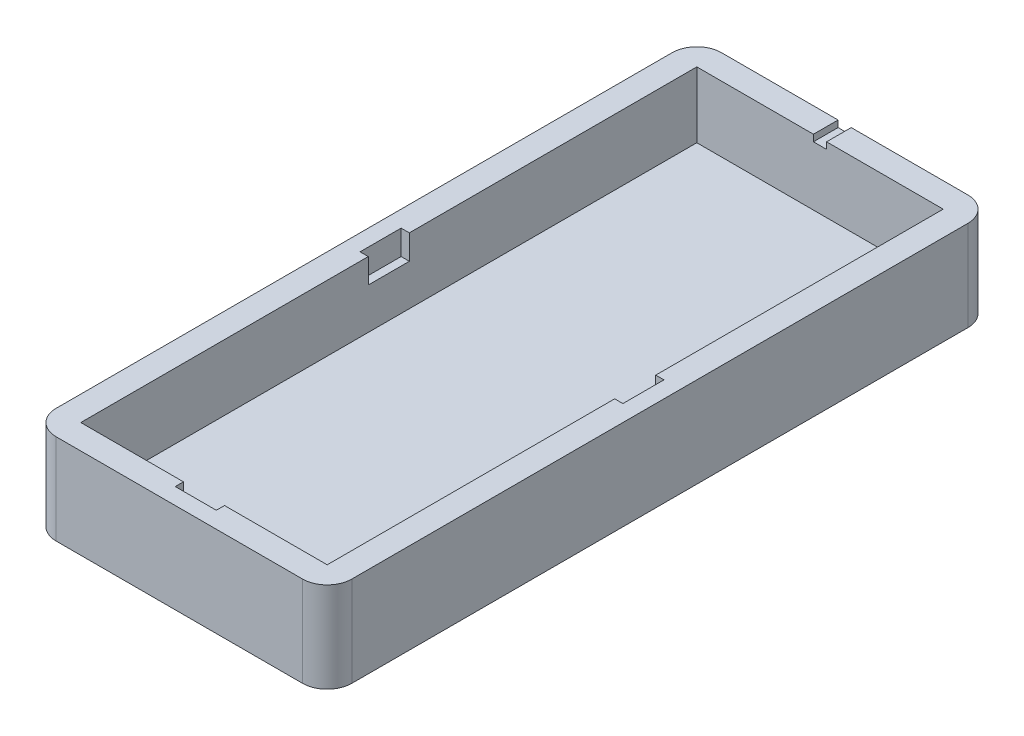
SolidWorks part; units mm, degrees
ref_plane "Front Plane" through (0, 0, 0) normal (0, 0, 1) x (1, 0, 0)
ref_plane "Top Plane" through (0, 0, 0) normal (0, 1, 0) x (1, 0, 0)
ref_plane "Right Plane" through (0, 0, 0) normal (1, 0, 0) x (0, 0, -1)
sketch "Sketch1" plane through (0, 0, 0) normal (0, 1, 0) x (1, 0, 0)
  line L1 (0, 0) -> (36, 0)
  line L2 (0, 0) -> (0, 81)
  line L3 (0, 81) -> (36, 81)
  line L4 (36, 0) -> (36, 81)
  dimension "D1" = 36
  dimension "D2" = 81
extrude "Boss-Extrude1" add sketch "Sketch1" along normal blind 11
sketch "Sketch2" plane through (0, 11, 0) normal (0, 1, 0) x (1, 0, 0)
  line L0 (36, 81) -> (0, 81) construction
  line L1 (3, 3) -> (33, 3)
  line L2 (3, 3) -> (3, 78)
  line L3 (3, 78) -> (33, 78)
  line L4 (33, 3) -> (33, 78)
  line L5 (0, 0) -> (36, 0) construction
  line L6 (0, 81) -> (0, 0) construction
  line L7 (36, 0) -> (36, 81) construction
  dimension "D1" = 3
  dimension "D2" = 3
  dimension "D3" = 3
  dimension "D4" = 3
extrude "Cut-Extrude1" cut sketch "Sketch2" against normal blind 8
fillet "Fillet1" radius 3 4 edges at (0, 5.5, 0) (36, 5.5, 0) (36, 5.5, -81) (0, 5.5, -81)
sketch "Sketch3" plane through (0, 11, 0) normal (0, 1, 0) x (1, 0, 0)
  line L0 (18, 81) -> (18, 78) construction
  line L1 (33, 81) -> (3, 81) construction
  line L2 (33, 78) -> (3, 78) construction
  line L3 (33, 78) -> (3, 78) construction
  line L4 (17.2, 81) -> (18.8, 81)
  line L5 (17.2, 81) -> (17.2, 78)
  line L6 (17.2, 78) -> (18.8, 78)
  line L7 (18.8, 81) -> (18.8, 78)
  dimension "D1" = 0.8
  dimension "D2" = 0.8
extrude "Cut-Extrude2" cut sketch "Sketch3" against normal blind 0.8
sketch "Sketch4" plane through (0, 11, 0) normal (0, 1, 0) x (1, 0, 0)
  line L0 (3, 78) -> (3, 3) construction
  line L1 (3, 43) -> (2, 43)
  line L2 (3, 43) -> (3, 38)
  line L3 (3, 38) -> (2, 38)
  line L4 (2, 43) -> (2, 38)
  line L5 (0, 40.5) -> (3, 40.5) construction
  line L6 (0, 78) -> (0, 3) construction
  line L7 (3, 78) -> (3, 3) construction
  line L8 (2, 40.5) -> (3, 40.5) construction
  line L9 (33, 40.5) -> (36, 40.5) construction
  line L10 (33, 3) -> (33, 78) construction
  line L11 (36, 3) -> (36, 78) construction
  line L12 (33, 40.5) -> (34, 40.5) construction
  line L13 (33, 43) -> (34, 43)
  line L14 (33, 43) -> (33, 38)
  line L15 (33, 38) -> (34, 38)
  line L16 (34, 43) -> (34, 38)
  line L17 (18, 3) -> (18, 0) construction
  line L18 (3, 3) -> (33, 3) construction
  line L19 (3, 0) -> (33, 0) construction
  line L20 (18, 3) -> (18, 2) construction
  line L21 (15.5, 3) -> (20.5, 3)
  line L22 (15.5, 3) -> (15.5, 2)
  line L23 (15.5, 2) -> (20.5, 2)
  line L24 (20.5, 3) -> (20.5, 2)
  dimension "D1" = 1
  dimension "D2" = 5
  dimension "D3" = 1
  dimension "D4" = 5
  dimension "D5" = 1
  dimension "D6" = 5
extrude "Cut-Extrude3" cut sketch "Sketch4" against normal blind 3
